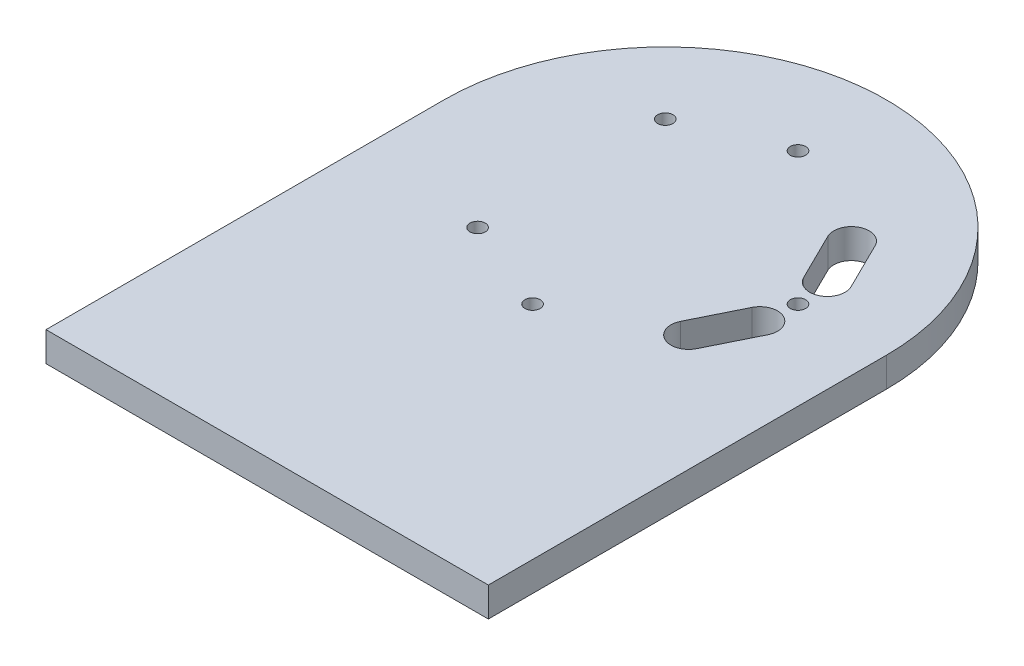
SolidWorks part; units mm, degrees
ref_plane "Front Plane" through (0, 0, 0) normal (0, 0, 1) x (1, 0, 0)
ref_plane "Top Plane" through (0, 0, 0) normal (0, 1, 0) x (1, 0, 0)
ref_plane "Right Plane" through (0, 0, 0) normal (1, 0, 0) x (0, 0, -1)
sketch "Sketch1" plane through (0, 0, 0) normal (0, 1, 0) x (1, 0, 0)
  line L0 (-28.575, 0) -> (0, 0) construction
  line L1 (0, 0) -> (-20.2056, -20.2056) construction
  line L2 (0, 0) -> (-20.2056, 20.2056) construction
  line L3 (27.6326, 7.2781) -> (22.5696, 17.5255) construction
  line L4 (24.2168, 5.5904) -> (19.1538, 15.8379)
  line L5 (31.0484, 8.9657) -> (25.9854, 19.2132)
  line L6 (27.6326, -7.2781) -> (22.5696, -17.5255) construction
  line L7 (24.2168, -5.5904) -> (19.1538, -15.8379)
  line L8 (31.0484, -8.9657) -> (25.9854, -19.2132)
  line L9 (0, -47.625) -> (0, -85.725)
  line L10 (-47.625, 0) -> (-47.625, -85.725)
  line L11 (-47.625, -85.725) -> (47.625, -85.725)
  line L12 (47.625, -85.725) -> (47.625, 0)
  circle A0 centre (0, 0) radius 28.575 construction
  circle A1 centre (0, 0) radius 47.625
  circle A2 centre (0, 28.575) radius 1.651
  circle A3 centre (0, -28.575) radius 1.651
  circle A4 centre (28.575, 0) radius 1.651
  circle A5 centre (-20.2056, 20.2056) radius 1.651
  circle A6 centre (-20.2056, -20.2056) radius 1.651
  arc A7 (24.2168, 5.5904) -> (31.0484, 8.9657) centre (27.6326, 7.2781) ccw
  arc A8 (25.9854, 19.2132) -> (19.1538, 15.8379) centre (22.5696, 17.5255) ccw
  arc A9 (24.2168, -5.5904) -> (31.0484, -8.9657) centre (27.6326, -7.2781) cw
  arc A10 (25.9854, -19.2132) -> (19.1538, -15.8379) centre (22.5696, -17.5255) cw
  point P17 (25.1011, 12.4018)
  point P24 (25.1011, -12.4018)
  dimension "D1" = 3.302
  dimension "D2" = 57.15
  dimension "D3" = 95.25
  dimension "D6" = 3.81
  dimension "D4" = 45
  dimension "D5" = 45
  dimension "D7" = 11.43
  dimension "D8" = 38.1
extrude "Boss-Extrude1" add sketch "Sketch1" along normal blind 6.35 contours A1 A2 A3 A4 A5 A6 A8 L5 A7 L4 L8 A10 L7 A9 | A1 L10 L11 L9 | A1 L9 L11 L12
